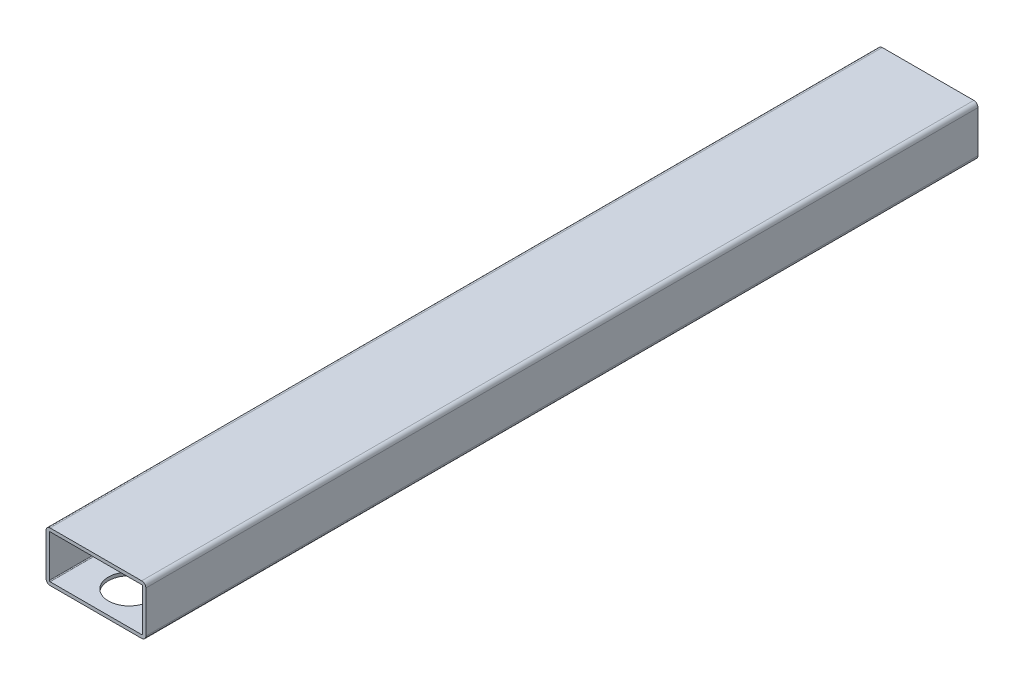
SolidWorks part; units mm, degrees
material "普通碳钢"
ref_plane "前视基准面" through (0, 0, 0) normal (0, 0, 1) x (1, 0, 0)
ref_plane "上视基准面" through (0, 0, 0) normal (0, 1, 0) x (1, 0, 0)
ref_plane "右视基准面" through (0, 0, 0) normal (1, 0, 0) x (0, 0, -1)
sketch "草图1" plane through (0, 0, 0) normal (0, 0, 1) x (1, 0, 0)
  line L0 (-55, 26) -> (55, 26)
  line L1 (-55, 30) -> (55, 30)
  line L2 (-60, 25) -> (-60, -25)
  line L3 (-55, -30) -> (55, -30)
  line L4 (60, 25) -> (60, -25)
  line L5 (-60, 30) -> (60, -30) construction
  line L6 (-60, -30) -> (60, 30) construction
  line L7 (56, 25) -> (56, -25)
  line L8 (-55, -26) -> (55, -26)
  line L9 (-56, 25) -> (-56, -25)
  arc A0 (55, 30) -> (60, 25) centre (55, 25) cw
  arc A1 (55, -30) -> (60, -25) centre (55, -25) ccw
  arc A2 (-60, -25) -> (-55, -30) centre (-55, -25) ccw
  arc A3 (-55, 30) -> (-60, 25) centre (-55, 25) ccw
  arc A4 (55, 26) -> (56, 25) centre (55, 25) cw
  arc A5 (55, -26) -> (56, -25) centre (55, -25) ccw
  arc A6 (-56, -25) -> (-55, -26) centre (-55, -25) ccw
  arc A7 (-55, 26) -> (-56, 25) centre (-55, 25) ccw
  point P0 (0, 0)
  dimension "D3" = 5
  dimension "D1" = 120
  dimension "D2" = 60
  dimension "D4" = 4
extrude "凸台-拉伸1" add sketch "草图1" along normal blind 1000
sketch "草图2" plane through (0, -30, 0) normal (0, -1, 0) x (1, 0, 0)
  line L0 (0, 1000) -> (0, 809.5001) construction
  line L1 (-55, 1000) -> (55, 1000) construction
  circle A0 centre (0, 960) radius 25
  dimension "D1" = 50
  dimension "D2" = 40
extrude "切除-拉伸1" cut sketch "草图2" against normal up to next
